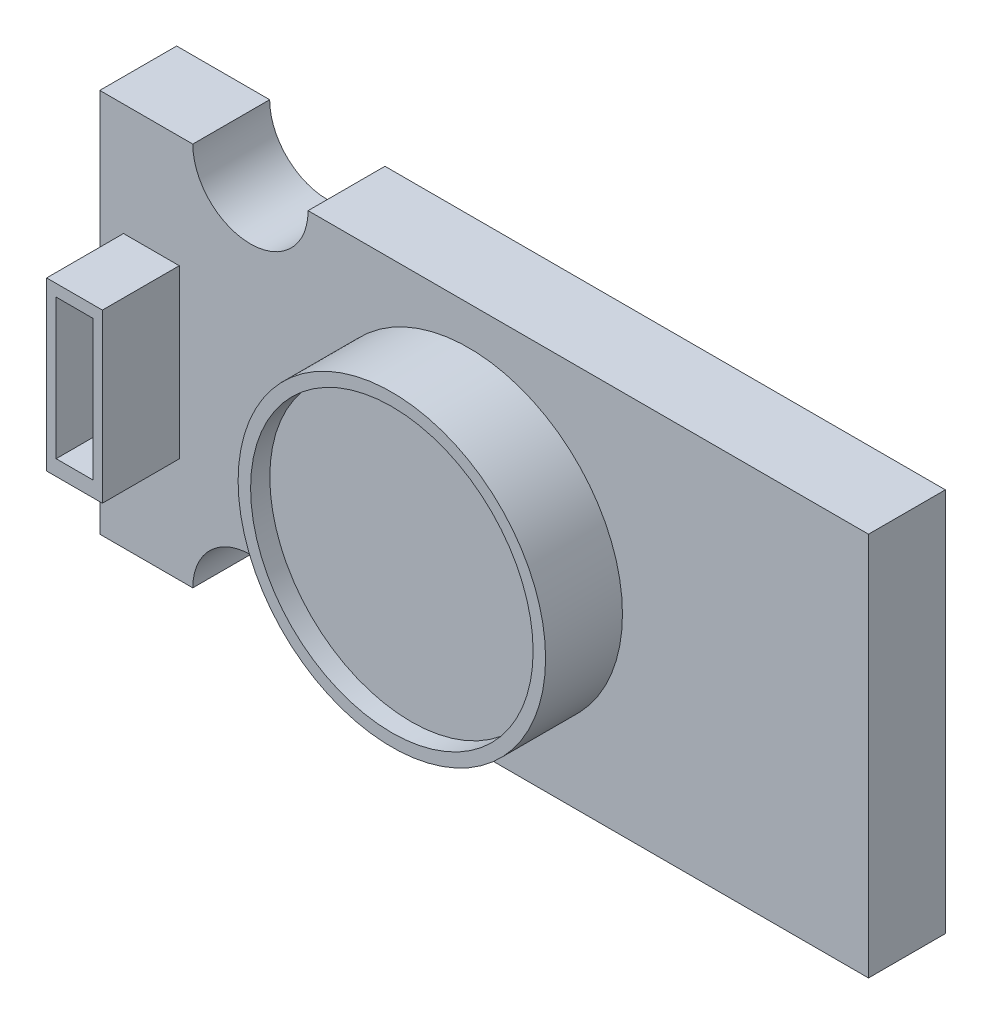
SolidWorks part; units mm, degrees
material "PE faible/moyenne densité"
ref_plane "Plan de face" through (0, 0, 0) normal (0, 0, 1) x (1, 0, 0)
ref_plane "Plan de dessus" through (0, 0, 0) normal (0, 1, 0) x (1, 0, 0)
ref_plane "Plan de droite" through (0, 0, 0) normal (1, 0, 0) x (0, 0, -1)
sketch "Esquisse1" plane through (0, 0, 0) normal (0, 0, 1) x (1, 0, 0)
  line L1 (-8.417, 8.6207) -> (11.583, 8.6207)
  line L2 (-8.417, 8.6207) -> (-8.417, -1.3793)
  line L3 (-8.417, -1.3793) -> (11.583, -1.3793)
  line L4 (11.583, 8.6207) -> (11.583, -1.3793)
  dimension "D1" = 20
  dimension "D2" = 10
extrude "Boss.-Extru.1" add sketch "Esquisse1" along normal blind 2
sketch "Esquisse2" plane through (0, 0, 2) normal (0, 0, 1) x (1, 0, 0)
  line L0 (11.583, 8.6207) -> (-8.417, 8.6207) construction
  line L1 (-8.417, -1.3793) -> (11.583, -1.3793) construction
  circle A1 centre (-4.4974, 8.6207) radius 1.5
  circle A2 centre (-4.4974, -1.3793) radius 1.5
extrude "Enlèv. mat.-Extru.1" cut sketch "Esquisse2" against normal blind 2
sketch "Esquisse3" plane through (0, 0, 2) normal (0, 0, 1) x (1, 0, 0)
  line L2 (-8.417, 3.6207) -> (11.583, 3.6207) construction
  line L3 (-8.417, 8.6207) -> (-8.417, -1.3793) construction
  line L4 (11.583, -1.3793) -> (11.583, 8.6207) construction
  circle A0 centre (1.1817, 3.6207) radius 4
extrude "Boss.-Extru.2" add sketch "Esquisse3" along normal blind 2
sketch "Esquisse4" plane through (0, 0, 4) normal (0, 0, 1) x (1, 0, 0)
  circle A0 centre (1.1817, 3.6207) radius 3.6754
extrude "Enlèv. mat.-Extru.2" cut sketch "Esquisse4" against normal blind 0.5
sketch "Esquisse5" plane through (0, 0, 2) normal (0, 0, 1) x (1, 0, 0)
  line L1 (-7.7999, 5.7041) -> (-6.3493, 5.7041)
  line L2 (-7.7999, 5.7041) -> (-7.7999, 1.3521)
  line L3 (-7.7999, 1.3521) -> (-6.3493, 1.3521)
  line L4 (-6.3493, 5.7041) -> (-6.3493, 1.3521)
extrude "Boss.-Extru.3" add sketch "Esquisse5" along normal blind 2
sketch "Esquisse6" plane through (0, 0, 4) normal (0, 0, 1) x (1, 0, 0)
  line L1 (-7.553, 5.3954) -> (-6.5962, 5.3954)
  line L2 (-7.553, 5.3954) -> (-7.553, 1.7534)
  line L3 (-7.553, 1.7534) -> (-6.5962, 1.7534)
  line L4 (-6.5962, 5.3954) -> (-6.5962, 1.7534)
extrude "Enlèv. mat.-Extru.3" cut sketch "Esquisse6" against normal blind 1.5
